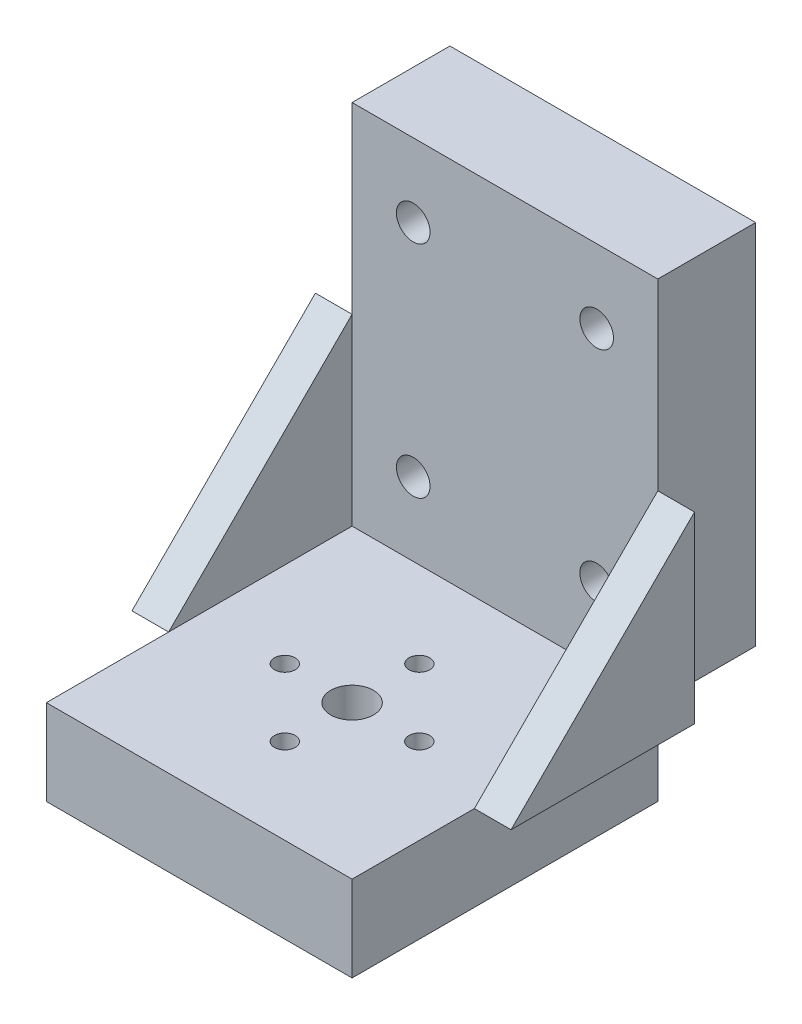
SolidWorks part; units mm, degrees
material "ABS"
ref_plane "Front Plane" through (0, 0, 0) normal (0, 0, 1) x (1, 0, 0)
ref_plane "Top Plane" through (0, 0, 0) normal (0, 1, 0) x (1, 0, 0)
ref_plane "Right Plane" through (0, 0, 0) normal (1, 0, 0) x (0, 0, -1)
sketch "Sketch1" plane through (0, 0, 0) normal (0, 1, 0) x (1, 0, 0)
  line L1 (-25, -25) -> (25, -25)
  line L2 (-25, -25) -> (-25, 25)
  line L3 (-25, 25) -> (25, 25)
  line L4 (25, -25) -> (25, 25)
  line L5 (-25, -25) -> (25, 25) construction
  line L6 (-25, 25) -> (25, -25) construction
  circle A0 centre (0, 0) radius 3.5
  point P0 (0, 0)
  dimension "D3" = 7
  dimension "D1" = 50
  dimension "D2" = 50
extrude "Motor Base" add sketch "Sketch1" along normal blind 14
sketch "Sketch2" plane through (25, 0, 0) normal (1, 0, 0) x (0, 0, -1)
  line L1 (25, 14) -> (41, 14)
  line L2 (25, 14) -> (25, 74)
  line L3 (25, 74) -> (41, 74)
  line L4 (41, 14) -> (41, 74)
  dimension "D1" = 60
  dimension "D2" = 16
extrude "Wall Mount" add sketch "Sketch2" against normal through all separate body
sketch "Sketch6" plane through (0, 14, 0) normal (0, 1, 0) x (1, 0, 0)
  line L0 (0, 25) -> (0, -25) construction
  line L1 (25, 25) -> (-25, 25) construction
  line L2 (-25, -25) -> (25, -25) construction
  line L3 (-25, 0) -> (25, 0) construction
  line L4 (-25, 25) -> (-25, -25) construction
  line L5 (25, -25) -> (25, 25) construction
  circle A0 centre (0, 11) radius 1.7
  circle A1 centre (11, 0) radius 1.7
  circle A2 centre (0, -11) radius 1.7
  circle A3 centre (-11, 0) radius 1.7
  dimension "D1" = 3.4
  dimension "D2" = 11
  dimension "D3" = 11
  dimension "D4" = 11
  dimension "D5" = 11
extrude "Motor Holes" cut sketch "Sketch6" against normal through all
sketch "Sketch8" plane through (0, 0, -25) normal (0, 0, 1) x (1, 0, 0)
  line L0 (-25, 74) -> (-25, 14) construction
  line L1 (-25, 74) -> (25, 74) construction
  line L2 (25, 74) -> (25, 14) construction
  line L3 (-25, 14) -> (25, 14) construction
  circle A0 centre (-15, 62) radius 2.75
  circle A1 centre (15, 62) radius 2.75
  circle A2 centre (15, 26) radius 2.75
  circle A3 centre (-15, 26) radius 2.75
  point P16 (-38.7514, 9.9678)
  dimension "D1" = 5.5
  dimension "D2" = 10
  dimension "D3" = 12
  dimension "D4" = 10
  dimension "D5" = 12
  dimension "D6" = 10
  dimension "D7" = 12
  dimension "D8" = 10
  dimension "D9" = 12
extrude "Wall Holes" cut sketch "Sketch8" against normal through all
ref_plane "Plane1" through (-25, 14, -25) normal (0, -1, 0) x (-1, 0, 0)
sketch "Sketch10" plane through (-25, 0, 0) normal (-1, 0, 0) x (0, 0, 1)
  line L0 (-25, 14) -> (5, 14)
  line L1 (-41.5, 14) -> (-8.5, 14) construction
  line L2 (-25, 14) -> (-25, 0) construction
  line L3 (5, 14) -> (-25, 44)
  line L4 (-25, 74) -> (-25, 14) construction
  line L5 (-25, 44) -> (-25, 14)
  dimension "D1" = 30
  dimension "D2" = 30
extrude "gusset1" add sketch "Sketch10" along normal blind 6 separate body
mirror "Mirror2" about plane through (0, 0, 0) normal (1, 0, 0) of bodies 106
